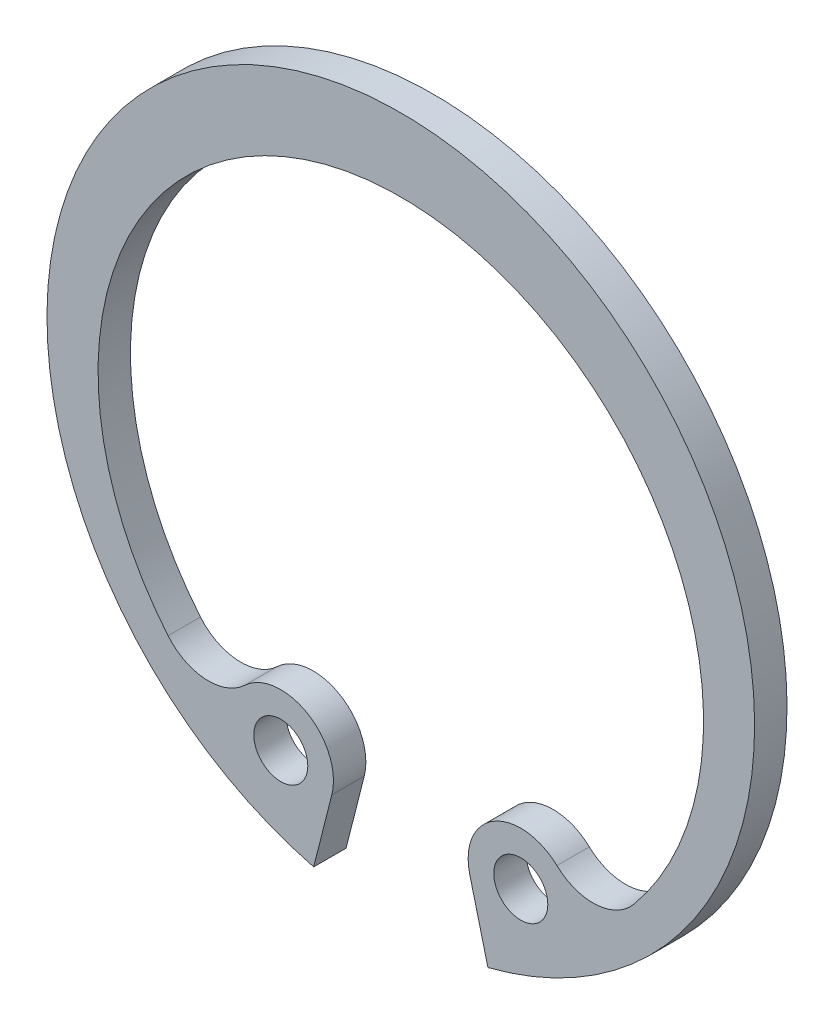
SolidWorks part; units mm, degrees
extrude "Body" add sketch "BodySke" against normal blind 1.2
sketch "BodySke" plane through (0, 0, 0) normal (0, 0, 1) x (1, 0, 0)
  line L0 (-1.5431, 0) -> (1.5431, 0) construction
  line L1 (0, 0) -> (0, 10.4) construction
  line L2 (3.2259, -12.6966) -> (2.5532, -10.0489)
  line L3 (-3.2259, -12.6966) -> (-2.5532, -10.0489)
  line L4 (0, 0) -> (9.5185, -9.0005) construction
  line L5 (0, 0) -> (-9.5185, -9.0005) construction
  line L6 (-4.1969, -8.5996) -> (-4.6894, -10.538) construction
  line L7 (4.2583, -8.8413) -> (4.628, -10.2962) construction
  arc A0 (-2.5532, -10.0489) -> (-5.7807, -8.1498) centre (-4.4431, -9.5688) ccw
  arc A1 (5.7807, -8.1498) -> (2.5532, -10.0489) centre (4.4431, -9.5688) ccw
  arc A2 (8.5376, -8.0729) -> (-8.5376, -8.0729) centre (0, -0.8094) ccw construction
  arc A3 (3.2259, -12.6966) -> (-3.2259, -12.6966) centre (0, 0) ccw
  circle A4 centre (4.4431, -9.5688) radius 1
  circle A5 centre (-4.4431, -9.5688) radius 1
  circle A6 centre (4.4431, -9.5688) radius 1.95 construction
  arc A7 (8.6174, -7.978) -> (-8.6174, -7.978) centre (0, -0.8094) ccw
  arc A8 (-4.4431, -9.5688) -> (4.4431, -9.5688) centre (0, 0) ccw construction
  arc A9 (-8.6174, -7.978) -> (-5.7807, -8.1498) centre (-7.1183, -6.7309) ccw
  arc A10 (5.7807, -8.1498) -> (8.6174, -7.978) centre (7.1183, -6.7309) ccw
  dimension "HoleDia" = 2
  dimension "HoleOffsetRad" = 10.55
  dimension "GrooveDia" = 26.2
  dimension "TipRad" = 1.95
  dimension "FilletRad" = 1.95
  dimension "LargeRad" = 10.4
  dimension "SmallRad" = 11.75
  dimension "SmallAngle" = 93.205
  dimension "GapAngle" = 28.511
ref_plane "Plane1" through (0, 0, 0) normal (0, 0, 1) x (1, 0, 0)
ref_plane "Plane2" through (0, 0, 0) normal (0, 1, 0) x (1, 0, 0)
ref_plane "Plane3" through (0, 0, 0) normal (1, 0, 0) x (0, 0, -1)
sketch "Clipboard" plane through (0, 0, 0) normal (0, 0, 1) x (1, 0, 0)
  line L0 (0, 0) -> (2.7, 0)
  line L1 (0, 0) -> (0, 1.35)
  line L2 (0, 0) -> (0, -4.5)
  circle A0 centre (0, 0) radius 1
  circle A1 centre (0, 0) radius 12.5
  dimension "HoleDia" = 2
  dimension "BoreDia" = 25
  dimension "LargeSection" = 2.7
  dimension "SmallSection" = 1.35
  dimension "LugSection" = 4.5
sketch "ModLugSke" plane through (0, 0, 0) normal (0, 0, 1) x (1, 0, 0)
  line L0 (3.2259, -12.6966) -> (2.1422, -8.4315)
  line L1 (-3.2259, -12.6966) -> (-2.1422, -8.4315)
  line L2 (7.1102, -4.8379) -> (10.8306, -7.3694) construction
  line L3 (-7.1102, -4.8379) -> (-10.8306, -7.3694) construction
  line L4 (-3.2259, -12.6966) -> (-2.5532, -10.0489) construction
  line L5 (2.5532, -10.0489) -> (3.2259, -12.6966) construction
  line L6 (0, 0) -> (0, -18.0732) construction
  line L7 (9.6212, -6.5465) -> (10.8306, -7.3694)
  line L8 (-10.8306, -7.3694) -> (-9.6212, -6.5465)
  arc A0 (3.2259, -12.6966) -> (10.8306, -7.3694) centre (0, 0) ccw
  arc A1 (-4.9183, -7.0548) -> (-2.2134, -8.3103) centre (0, 0) ccw
  arc A2 (3.2259, -12.6966) -> (-3.2259, -12.6966) centre (0, 0) ccw construction
  arc A3 (5.7807, -8.1498) -> (2.5532, -10.0489) centre (4.4431, -9.5688) ccw construction
  arc A4 (-4.9183, -7.0548) -> (-5.0435, -7.0636) centre (-4.9754, -7.1369) ccw
  arc A5 (-9.6212, -6.5465) -> (-5.0435, -7.0636) centre (-7.1102, -4.8379) ccw
  arc A6 (8.6174, -7.978) -> (-8.6174, -7.978) centre (0, -0.8094) ccw construction
  arc A7 (5.0435, -7.0636) -> (9.6212, -6.5465) centre (7.1102, -4.8379) ccw
  arc A8 (2.2134, -8.3103) -> (4.9183, -7.0548) centre (0, 0) ccw
  arc A9 (-10.8306, -7.3694) -> (-3.2259, -12.6966) centre (0, 0) ccw
  circle A10 centre (-4.4431, -9.5688) radius 1
  circle A11 centre (-4.4431, -9.5688) radius 1 construction
  circle A12 centre (4.4431, -9.5688) radius 1
  circle A13 centre (4.4431, -9.5688) radius 1 construction
  arc A14 (-2.2134, -8.3103) -> (-2.1422, -8.4315) centre (-2.2392, -8.4069) cw
  arc A15 (2.2134, -8.3103) -> (2.1422, -8.4315) centre (2.2392, -8.4069) ccw
  arc A16 (4.9183, -7.0548) -> (5.0435, -7.0636) centre (4.9754, -7.1369) cw
  point P43 (2.1178, -8.3352)
  dimension "D1" = 0.1
extrude "ModLug" [suppressed] add sketch "ModLugSke" against normal through all
sketch "UnlSke" [suppressed] plane through (0, 0, 0) normal (0, 0, 1) x (1, 0, 0)
  line L0 (2.1178, -8.3352) -> (3.2259, -12.6966)
  line L1 (-2.1178, -8.3352) -> (-3.2259, -12.6966)
  line L2 (-3.2259, -12.6966) -> (-2.1422, -8.4315) construction
  line L3 (2.1422, -8.4315) -> (3.2259, -12.6966) construction
  arc A0 (2.1178, -8.3352) -> (-2.1178, -8.3352) centre (0, 0) ccw
  arc A1 (3.2259, -12.6966) -> (-3.2259, -12.6966) centre (0, 0) ccw
  arc A2 (3.2259, -12.6966) -> (-3.2259, -12.6966) centre (0, 0) ccw construction
  circle A4 centre (-4.4431, -9.5688) radius 1
  circle A5 centre (4.4431, -9.5688) radius 1
  circle A6 centre (4.4431, -9.5688) radius 1 construction
  circle A7 centre (-4.4431, -9.5688) radius 1 construction
  arc A8 (2.2134, -8.3103) -> (4.9183, -7.0548) centre (0, 0) ccw construction
extrude "Unlug" [suppressed] add sketch "UnlSke" against normal through all
equation "' \"BoreDia@Clipboard\" = 8"
equation "' \"Thickness@Body\" = 0.8"
equation "' \"GrooveDia@BodySke\" = 8.4"
equation "' \"LugSection@Clipboard\" = 2.4"
equation "' \"LargeSection@Clipboard\" = 1.1"
equation "' \"HoleDia@Clipboard\" = 1.0"
equation "' \"BoreDia@Clipboard\" = 25"
equation "' \"Thickness@Body\" = 1.2"
equation "' \"GrooveDia@BodySke\" = 26.2"
equation "' \"LugSection@Clipboard\" = 4.5"
equation "' \"LargeSection@Clipboard\" = 2.7"
equation "' \"HoleDia@Clipboard\" = 2"
equation "\"SmallSection@Clipboard\" = \"LargeSection@Clipboard\" * 0.5"
equation "\"TipRad@BodySke\" = (\"LugSection@Clipboard\" - (\"GrooveDia@BodySke\" / 2  -  \"BoreDia@Clipboard\" / 2 ) ) / 2"
equation "\"HoleOffsetRad@BodySke\" = (\"GrooveDia@BodySke\" / 2) - \"LugSection@Clipboard\"  + \"TipRad@BodySke\""
equation "\"LargeRad@BodySke\" =  \"GrooveDia@BodySke\" / 2 -  \"LargeSection@Clipboard\""
equation "\"SmallRad@BodySke\" =  \"GrooveDia@BodySke\" / 2 -  \"SmallSection@Clipboard\""
equation "\"HoleDia@BodySke\" =  \"HoleDia@Clipboard\""
equation "\"FilletRad@BodySke\" = \"TipRad@BodySke\" * 1.0"
equation "\"GapAngle@BodySke\" = 360 - 0.965 * 360 * ( \"BoreDia@Clipboard\" /  \"GrooveDia@BodySke\")"
equation "\"LugAng@ModLugSke\" = \"GapAngle@BodySke\"  + 2 * 360 * (\"LugSection@Clipboard\" / (\"BoreDia@Clipboard\" * 3.1416))"
